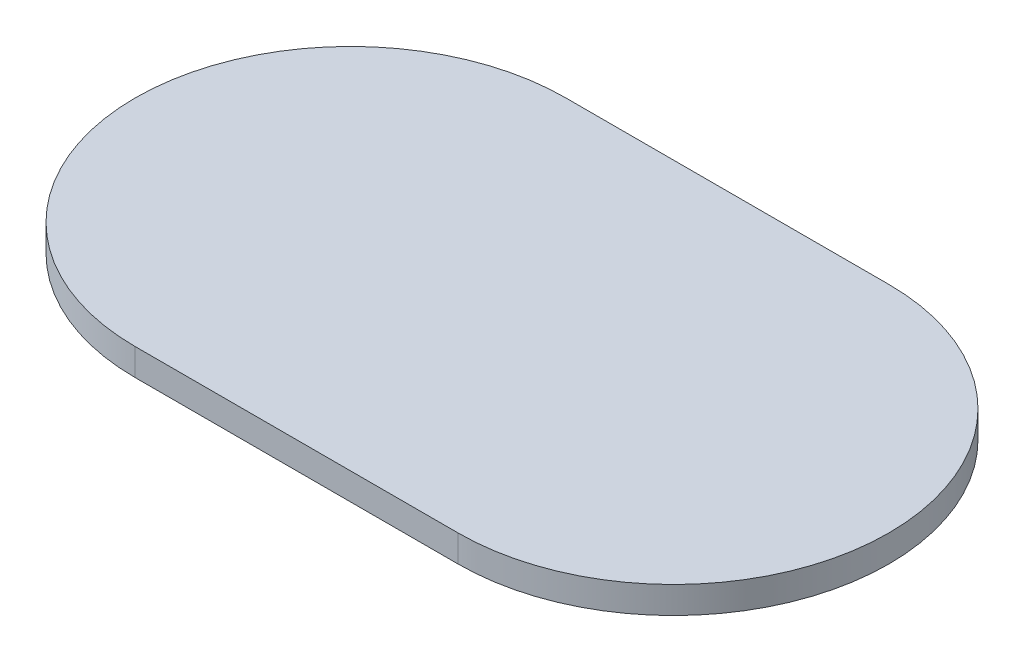
SolidWorks part; units mm, degrees
ref_plane "Front Plane" through (0, 0, 0) normal (0, 0, 1) x (1, 0, 0)
ref_plane "Top Plane" through (0, 0, 0) normal (0, 1, 0) x (1, 0, 0)
ref_plane "Right Plane" through (0, 0, 0) normal (1, 0, 0) x (0, 0, -1)
sketch "Sketch1" plane through (0, 0, 0) normal (0, 1, 0) x (1, 0, 0)
  line L0 (30, 0) -> (-30, 0)
  line L3 (30, 80) -> (-30, 80)
  arc A0 (30, 0) -> (30, 80) centre (30, 40) ccw
  arc A1 (-30, 80) -> (-30, 0) centre (-30, 40) ccw
extrude "Boss-Extrude1" add sketch "Sketch1" along normal blind 5
